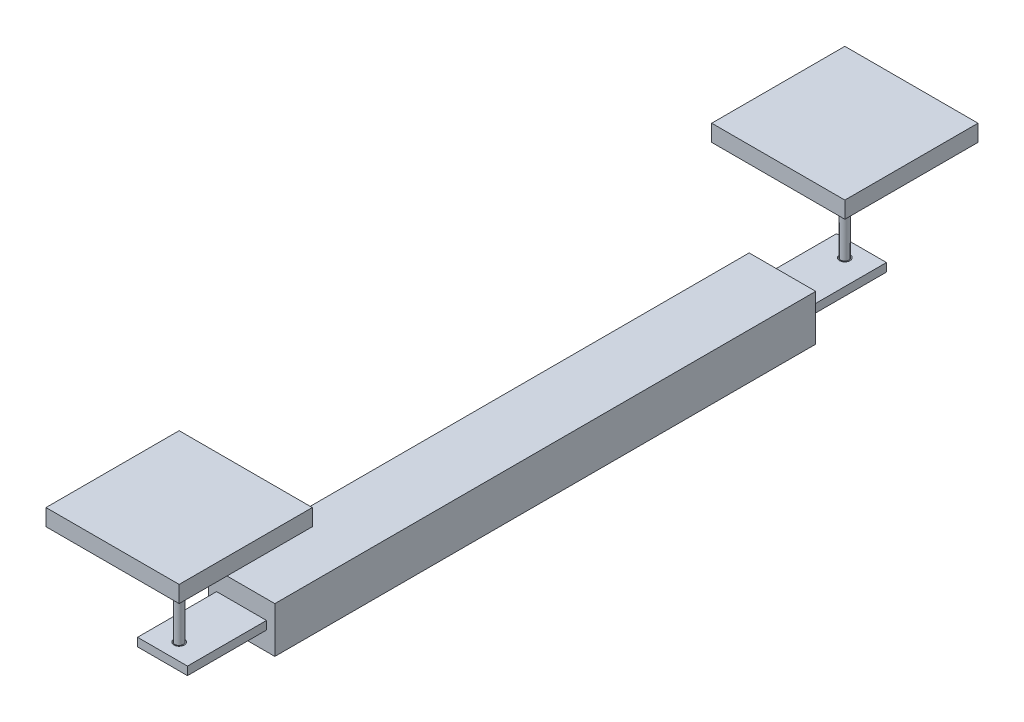
SolidWorks part; units mm, degrees
ref_plane "Front" through (0, 0, 0) normal (0, 0, 1) x (1, 0, 0)
ref_plane "Top" through (0, 0, 0) normal (0, 1, 0) x (1, 0, 0)
ref_plane "Right" through (0, 0, 0) normal (1, 0, 0) x (0, 0, -1)
sketch "Sketch2" plane through (0, 0, 0) normal (1, 0, 0) x (0, 0, -1)
  line L1 (-266.7, 3.175) -> (266.7, 3.175)
  line L2 (-266.7, 3.175) -> (-266.7, -3.175)
  line L3 (-266.7, -3.175) -> (266.7, -3.175)
  line L4 (266.7, 3.175) -> (266.7, -3.175)
  line L5 (-266.7, 3.175) -> (266.7, -3.175) construction
  line L6 (-266.7, -3.175) -> (266.7, 3.175) construction
  point P0 (0, 0)
  dimension "D1" = 533.4
  dimension "D2" = 6.35
extrude "Boss-Extrude1" add sketch "Sketch2" along normal mid plane 38.1
sketch "Sketch3" plane through (0, 0, 0) normal (1, 0, 0) x (0, 0, -1)
  line L1 (-206.375, 17.4625) -> (206.375, 17.4625)
  line L2 (-206.375, 17.4625) -> (-206.375, -17.4625)
  line L3 (-206.375, -17.4625) -> (206.375, -17.4625)
  line L4 (206.375, 17.4625) -> (206.375, -17.4625)
  line L5 (-206.375, 17.4625) -> (206.375, -17.4625) construction
  line L6 (-206.375, -17.4625) -> (206.375, 17.4625) construction
  point P0 (0, 0)
  dimension "D1" = 412.75
  dimension "D2" = 34.925
extrude "Boss-Extrude2" add sketch "Sketch3" along normal mid plane 50.8
sketch "Sketch4" plane through (0, 3.175, 0) normal (0, 1, 0) x (1, 0, 0)
  line L0 (0, 0) -> (0, 254) construction
  line L1 (0, 0) -> (0, -254) construction
  circle A0 centre (0, 254) radius 3.9688
  circle A1 centre (0, -254) radius 3.9688
  dimension "D3" = 7.9375
  dimension "D4" = 7.9375
  dimension "D1" = 254
  dimension "D2" = 254
extrude "Cut-Extrude1" cut sketch "Sketch4" against normal through all
sketch "Sketch5" plane through (0, 3.175, 0) normal (0, 1, 0) x (1, 0, 0)
  circle A0 centre (0, 254) radius 3.175
  circle A1 centre (0, -254) radius 3.175
  dimension "D1" = 6.35
extrude "Boss-Extrude3" add sketch "Sketch5" along normal blind 76.2 separate body
sketch "Sketch6" plane through (0, 79.375, 0) normal (0, 1, 0) x (1, 0, 0)
  line L1 (-50.8, 304.8) -> (50.8, 304.8)
  line L2 (-50.8, 304.8) -> (-50.8, 203.2)
  line L3 (-50.8, 203.2) -> (50.8, 203.2)
  line L4 (50.8, 304.8) -> (50.8, 203.2)
  line L5 (-50.8, 304.8) -> (50.8, 203.2) construction
  line L6 (-50.8, 203.2) -> (50.8, 304.8) construction
  line L7 (-50.8, -203.2) -> (50.8, -203.2)
  line L8 (-50.8, -203.2) -> (-50.8, -304.8)
  line L9 (-50.8, -304.8) -> (50.8, -304.8)
  line L10 (50.8, -203.2) -> (50.8, -304.8)
  line L11 (-50.8, -203.2) -> (50.8, -304.8) construction
  line L12 (-50.8, -304.8) -> (50.8, -203.2) construction
  point P0 (0, 254)
  point P6 (0, -254)
  dimension "D1" = 101.6
extrude "Boss-Extrude4" add sketch "Sketch6" along normal blind 12.7
